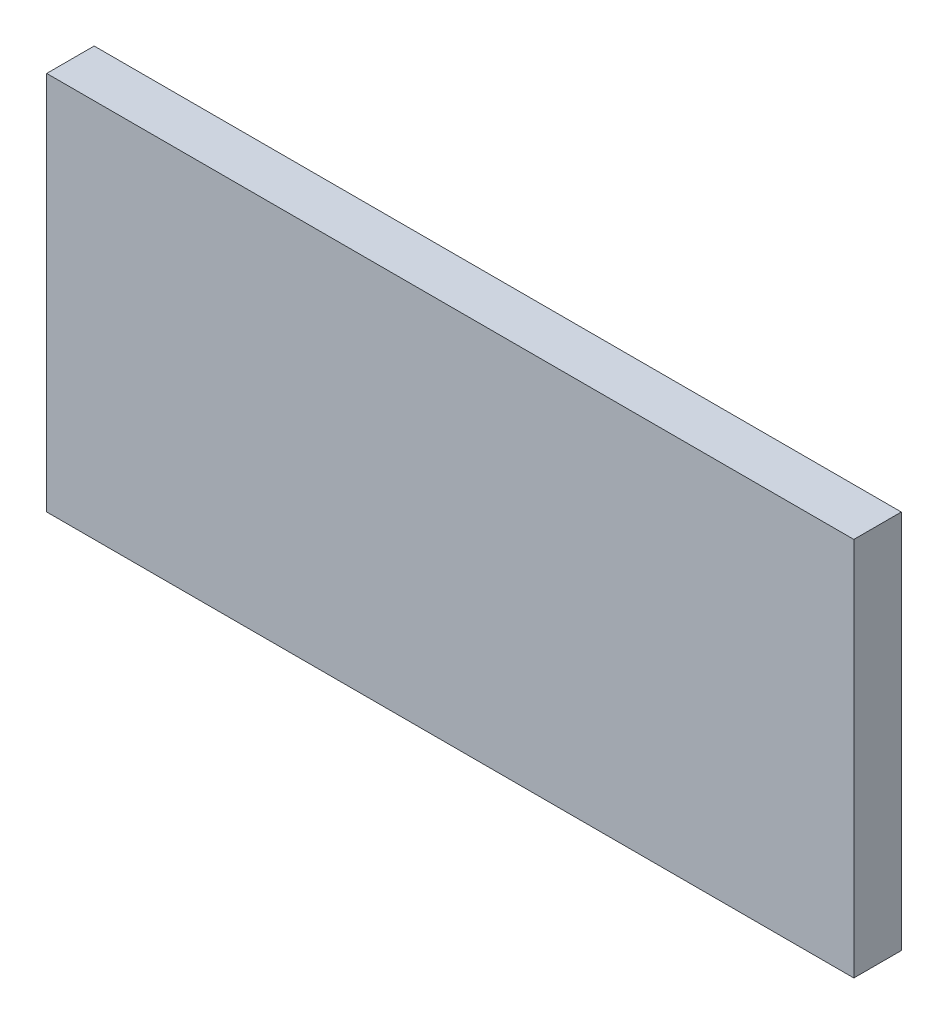
SolidWorks part; units mm, degrees
ref_plane "Plan de face" through (0, 0, 0) normal (0, 0, 1) x (1, 0, 0)
ref_plane "Plan de dessus" through (0, 0, 0) normal (0, 1, 0) x (1, 0, 0)
ref_plane "Plan de droite" through (0, 0, 0) normal (1, 0, 0) x (0, 0, -1)
sketch "Esquisse1" plane through (0, 0, 0) normal (0, 0, 1) x (1, 0, 0)
  line L1 (-42.5, 20) -> (42.5, 20)
  line L2 (-42.5, 20) -> (-42.5, -20)
  line L3 (-42.5, -20) -> (42.5, -20)
  line L4 (42.5, 20) -> (42.5, -20)
  line L5 (-42.5, 20) -> (42.5, -20) construction
  line L6 (-42.5, -20) -> (42.5, 20) construction
  point P0 (0, 0)
  dimension "D1" = 85
  dimension "D2" = 40
extrude "Boss.-Extru.1" add sketch "Esquisse1" along normal blind 5
